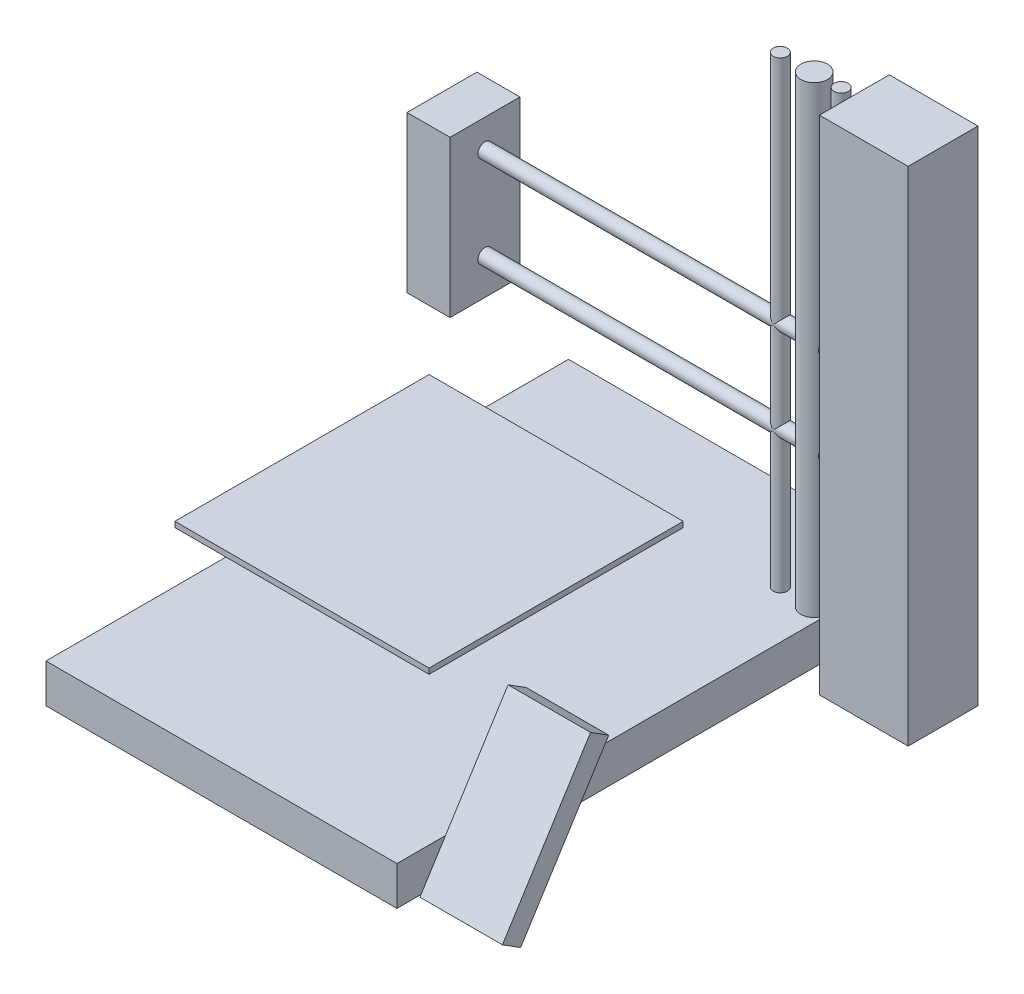
SolidWorks part; units mm, degrees
ref_plane "Front Plane" through (0, 0, 0) normal (0, 0, 1) x (1, 0, 0)
ref_plane "Top Plane" through (0, 0, 0) normal (0, 1, 0) x (1, 0, 0)
ref_plane "Right Plane" through (0, 0, 0) normal (1, 0, 0) x (0, 0, -1)
sketch "Sketch1" plane through (0, 0, 0) normal (0, 1, 0) x (1, 0, 0)
  line L0 (-165, 185) -> (165, -185) construction
  line L1 (-165, 185) -> (165, 185) construction
  line L2 (-165, 185) -> (-165, -185) construction
  line L3 (-165, -185) -> (165, -185) construction
  line L4 (165, 185) -> (165, -185) construction
  dimension "D1" = 330
  dimension "D2" = 370
sketch "Sketch2" plane through (0, 0, 0) normal (1, 0, 0) x (0, 0, -1)
  line L1 (-185, 177.8) -> (185, 177.8) construction
  line L2 (-185, 177.8) -> (-185, -177.8) construction
  line L3 (-185, -177.8) -> (185, -177.8) construction
  line L4 (185, 177.8) -> (185, -177.8) construction
  dimension "D1" = 355.6
sketch "Sketch4" plane through (0, 0, 0) normal (0, 0, 1) x (1, 0, 0)
  line L1 (-165, -150.2678) -> (83.5337, -150.2678)
  line L2 (-165, -150.2678) -> (-165, -177.8)
  line L3 (-165, -177.8) -> (83.5337, -177.8)
  line L4 (83.5337, -150.2678) -> (83.5337, -177.8)
extrude "Boss-Extrude2" add sketch "Sketch4" against normal up to vertex (185 mm away) and the other way up to vertex (185 mm away) up to point (0, -177.8, -185) other way up to point (0, -177.8, 185)
sketch "Sketch5" plane through (0, 0, 0) normal (0, 0, 1) x (1, 0, 0)
  line L1 (-168.7097, -113.9713) -> (11.2903, -113.9713)
  line L2 (-168.7097, -113.9713) -> (-168.7097, -117.8429)
  line L3 (-168.7097, -117.8429) -> (11.2903, -117.8429)
  line L4 (11.2903, -113.9713) -> (11.2903, -117.8429)
  dimension "D1" = 180
extrude "Boss-Extrude3" add sketch "Sketch5" along normal mid plane 180 separate body
sketch "Sketch6" plane through (0, 0, 0) normal (0, 1, 0) x (1, 0, 0)
  line L0 (165, 185) -> (165, -185) construction
  line L1 (165, 145.0373) -> (102.2072, 145.0373)
  line L2 (165, 145.0373) -> (165, 95.5523)
  line L3 (165, 95.5523) -> (102.2072, 95.5523)
  line L4 (102.2072, 145.0373) -> (102.2072, 95.5523)
  line L5 (165, 120.2948) -> (31.8664, 120.2948) construction
  circle A0 centre (92.851, 120.2948) radius 5.0253
  circle A1 centre (49.7412, 120.2948) radius 5.0253
  circle A2 centre (73.7144, 120.2948) radius 9.4415
extrude "Boss-Extrude4" add sketch "Sketch6" against normal up to vertex (177.8 mm away) and the other way up to vertex (177.8 mm away) other way up to point (0, 177.8, -185)
sketch "Sketch7" plane through (102.2072, 0, 0) normal (-1, 0, 0) x (0, 0, 1)
  line L0 (-120.2948, 177.8) -> (-120.2948, -177.8) construction
  line L1 (-145.0373, 177.8) -> (-95.5523, 177.8) construction
  line L2 (185, -177.8) -> (-185, -177.8) construction
  circle A0 centre (-120.2948, 13.3087) radius 5.0253
  circle A1 centre (-120.2948, -51.5892) radius 5.0727
extrude "Boss-Extrude5" add sketch "Sketch7" along normal blind 292.1
sketch "Sketch8" plane through (-189.8928, 0, 0) normal (-1, 0, 0) x (0, 0, 1)
  line L0 (-145.0373, -177.8) -> (-145.0373, 177.8) construction
  line L1 (-145.0373, 33.4097) -> (-95.5523, 33.4097)
  line L2 (-145.0373, 33.4097) -> (-145.0373, -77.1797)
  line L3 (-145.0373, -77.1797) -> (-95.5523, -77.1797)
  line L4 (-95.5523, 33.4097) -> (-95.5523, -77.1797)
  line L5 (-120.2948, -77.1797) -> (-120.2948, 33.4097) construction
  circle A0 centre (-120.2948, 13.3087) radius 5.0253 construction
  point P8 (-120.2948, 13.3087)
extrude "Boss-Extrude6" add sketch "Sketch8" against normal blind 30.48
ref_plane "Plane1" through (88.9, 0, 0) normal (1, 0, 0) x (0, 0, -1)
sketch "Sketch9" plane through (88.9, 0, 0) normal (1, 0, 0) x (0, 0, -1)
  line L0 (-103.8613, -77.6574) -> (-166.2848, -176.7174)
  line L1 (-166.2848, -176.7174) -> (-179.1784, -168.5924)
  line L2 (-179.1784, -168.5924) -> (-116.7548, -69.5324)
  line L3 (-116.7548, -69.5324) -> (-103.8613, -77.6574)
  line L4 (-166.2848, -176.7174) -> (249.6106, -176.7174) construction
  dimension "D1" = 99.06
  dimension "D2" = 49.53
  dimension "D3" = 15.24
extrude "Boss-Extrude7" add sketch "Sketch9" along normal blind 63.5 separate body
sketch "Sketch10" plane through (88.9, 0, 0) normal (-1, 0, 0) x (0, 0, 1)
  line L1 (227.6104, -34.4058) -> (99.9302, -34.4058)
  line L2 (227.6104, -34.4058) -> (227.6104, -179.2035)
  line L3 (227.6104, -179.2035) -> (99.9302, -179.2035)
  line L4 (99.9302, -34.4058) -> (99.9302, -179.2035)
extrude "Cut-Extrude1" cut sketch "Sketch10" against normal blind 5.08
